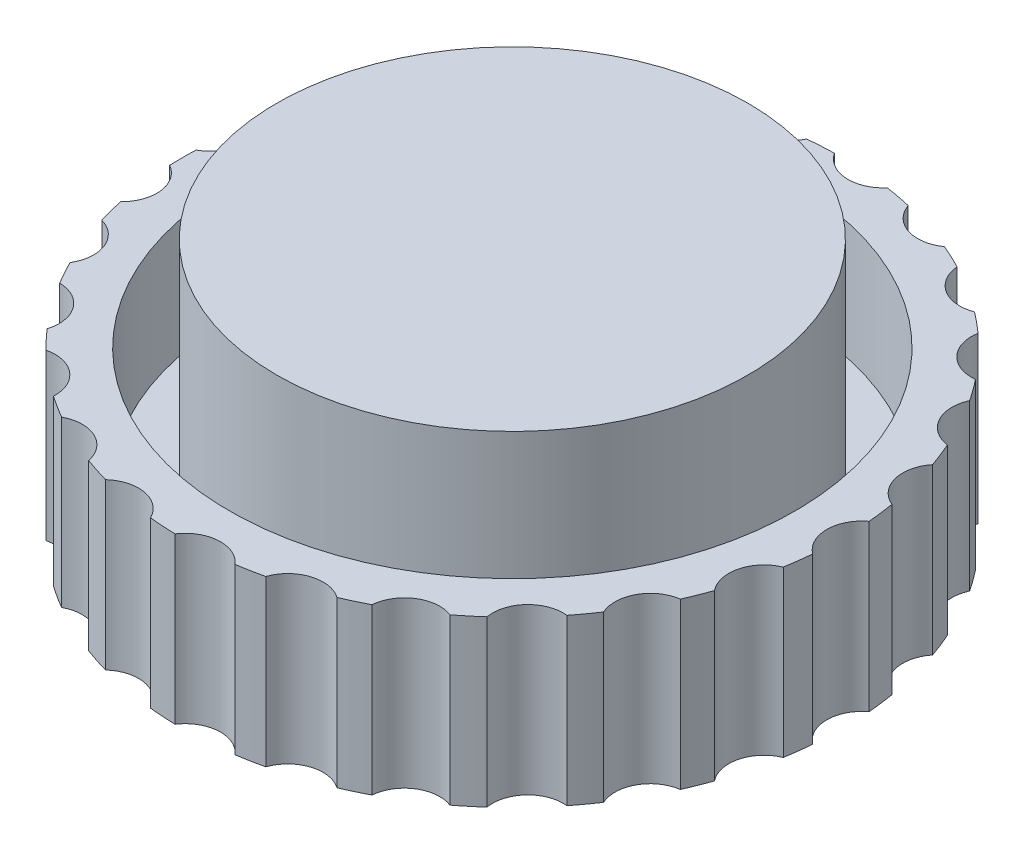
SolidWorks part; units mm, degrees
material "BUTYL"
ref_plane "Plan de face" through (0, 0, 0) normal (0, 0, 1) x (1, 0, 0)
ref_plane "Plan de dessus" through (0, 0, 0) normal (0, 1, 0) x (1, 0, 0)
ref_plane "Plan de droite" through (0, 0, 0) normal (1, 0, 0) x (0, 0, -1)
sketch "Esquisse1" plane through (0, 0, 0) normal (0, 0, 1) x (1, 0, 0)
  line L0 (0, 0) -> (0, 14) construction
  line L1 (0, 0) -> (-14, 0)
  line L2 (-14, 0) -> (-14, 7)
  line L3 (-14, 7) -> (-12, 7)
  line L4 (-12, 7) -> (-12, 2)
  line L5 (-12, 2) -> (-10, 2)
  line L6 (-10, 2) -> (-10, 11)
  line L7 (-10, 11) -> (0, 11)
  line L8 (0, 0) -> (0, 11)
  dimension "D1" = 2
  dimension "D2" = 14
  dimension "D3" = 2
  dimension "D4" = 4
  dimension "D5" = 5
  dimension "D6" = 7
revolve "Révolution1" add sketch "Esquisse1" angle 360 about L0
sketch "Esquisse2" plane through (0, 7, 0) normal (0, 1, 0) x (1, 0, 0)
  circle A0 centre (14.849, 0) radius 1.5
  circle A1 centre (14.3825, -3.6928) radius 1.5
  circle A2 centre (13.0123, -7.1536) radius 1.5
  circle A3 centre (10.8244, -10.1648) radius 1.5
  circle A4 centre (7.9565, -12.5374) radius 1.5
  circle A5 centre (4.5886, -14.1222) radius 1.5
  circle A6 centre (0.9324, -14.8197) radius 1.5
  circle A7 centre (-2.7824, -14.586) radius 1.5
  circle A8 centre (-6.3224, -13.4358) radius 1.5
  circle A9 centre (-9.4651, -11.4413) radius 1.5
  circle A10 centre (-12.0131, -8.728) radius 1.5
  circle A11 centre (-13.8062, -5.4663) radius 1.5
  circle A12 centre (-14.7319, -1.8611) radius 1.5
  circle A13 centre (-14.7319, 1.8611) radius 1.5
  circle A14 centre (-13.8062, 5.4663) radius 1.5
  circle A15 centre (-12.0131, 8.728) radius 1.5
  circle A16 centre (-9.4651, 11.4413) radius 1.5
  circle A17 centre (-6.3224, 13.4358) radius 1.5
  circle A18 centre (-2.7824, 14.586) radius 1.5
  circle A19 centre (0.9324, 14.8197) radius 1.5
  circle A20 centre (4.5886, 14.1222) radius 1.5
  circle A21 centre (7.9565, 12.5374) radius 1.5
  circle A22 centre (10.8244, 10.1648) radius 1.5
  circle A23 centre (13.0123, 7.1536) radius 1.5
  circle A24 centre (14.3825, 3.6928) radius 1.5
  point P53 (0, 0)
  dimension "D1" = 3
  dimension "D2" = 25
extrude "Enlèv. mat.-Extru.1" cut sketch "Esquisse2" against normal up to next
